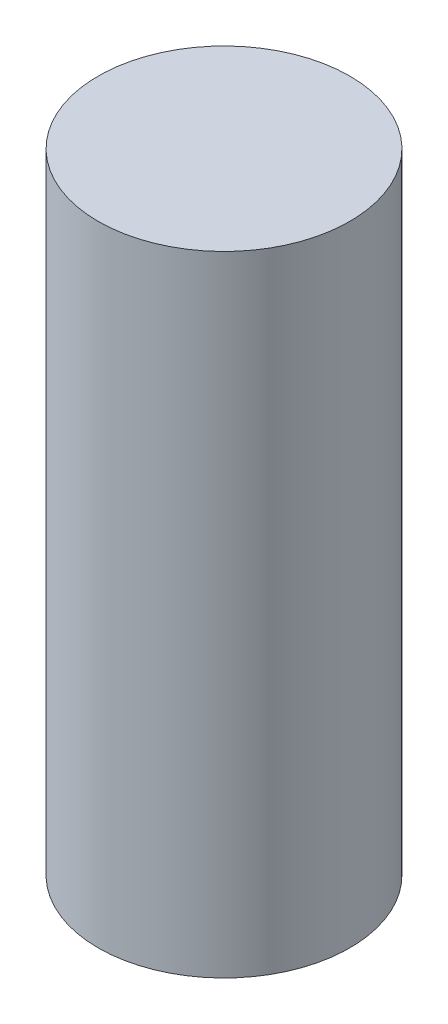
SolidWorks part; units mm, degrees
ref_plane "Front Plane" through (0, 0, 0) normal (0, 0, 1) x (1, 0, 0)
ref_plane "Top Plane" through (0, 0, 0) normal (0, 1, 0) x (1, 0, 0)
ref_plane "Right Plane" through (0, 0, 0) normal (1, 0, 0) x (0, 0, -1)
sketch "Sketch1" plane through (0, 0, 0) normal (0, 1, 0) x (1, 0, 0)
  circle A0 centre (0, 0) radius 0.1
extrude "Boss-Extrude1" add sketch "Sketch1" along normal blind 0.5
